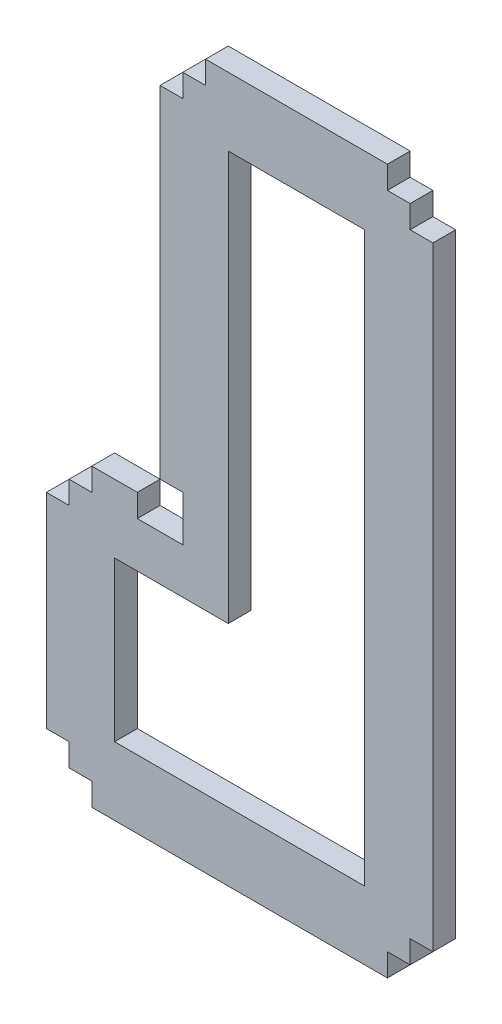
SolidWorks part; units mm, degrees
ref_plane "Front Plane" through (0, 0, 0) normal (0, 0, 1) x (1, 0, 0)
ref_plane "Top Plane" through (0, 0, 0) normal (0, 1, 0) x (1, 0, 0)
ref_plane "Right Plane" through (0, 0, 0) normal (1, 0, 0) x (0, 0, -1)
sketch "Sketch1" plane through (0, 0, 0) normal (0, 0, 1) x (1, 0, 0)
  line L0 (12.7, -69.85) -> (19.05, -69.85)
  line L1 (101.6, -69.85) -> (19.05, -69.85) construction
  line L2 (107.95, -76.2) -> (107.95, 120.65) construction
  line L3 (107.95, -69.85) -> (107.95, -63.5)
  line L4 (107.95, 114.3) -> (101.6, 114.3)
  line L5 (44.45, 114.3) -> (44.45, 107.95)
  line L6 (44.45, 0) -> (31.75, 0)
  line L7 (12.7, 0) -> (12.7, -6.35)
  line L8 (101.6, -76.2) -> (19.05, -76.2) construction
  line L9 (107.95, 107.95) -> (107.95, 114.3)
  line L10 (19.05, -69.85) -> (19.05, -76.2)
  line L11 (19.05, -76.2) -> (101.6, -76.2)
  line L12 (101.6, -69.85) -> (101.6, -76.2)
  line L13 (114.3, -69.85) -> (114.3, -76.2) construction
  line L14 (107.95, -63.5) -> (114.3, -63.5)
  line L15 (12.7, -63.5) -> (12.7, -69.85)
  line L16 (107.95, 107.95) -> (114.3, 107.95)
  line L17 (114.3, -63.5) -> (114.3, 107.95)
  line L18 (50.8, 120.65) -> (101.6, 120.65) construction
  line L20 (101.6, 114.3) -> (101.6, 120.65)
  line L21 (101.6, 120.65) -> (50.8, 120.65)
  line L22 (50.8, 114.3) -> (50.8, 120.65)
  line L23 (38.1, 114.3) -> (38.1, 31.75) construction
  line L24 (44.45, 107.95) -> (38.1, 107.95)
  line L25 (50.8, 114.3) -> (44.45, 114.3)
  line L26 (44.45, 12.7) -> (38.1, 12.7)
  line L27 (38.1, 107.95) -> (38.1, 12.7)
  line L28 (-38.1, 6.35) -> (6.35, 6.35) construction
  line L29 (12.7, -63.5) -> (6.35, -63.5)
  line L30 (19.05, 0) -> (12.7, 0)
  line L31 (12.7, -6.35) -> (6.35, -6.35)
  line L32 (6.35, -63.5) -> (6.35, -6.35)
  line L33 (44.45, 12.7) -> (44.45, 0)
  line L34 (19.05, 0) -> (19.05, 6.35)
  line L35 (19.05, 6.35) -> (31.75, 6.35)
  line L36 (31.75, 0) -> (31.75, 6.35)
  line L37 (101.6, -69.85) -> (107.95, -69.85)
  dimension "D1" = 6.35
  dimension "D2" = 6.35
  dimension "D3" = 6.35
  dimension "D4" = 6.35
  dimension "D5" = 6.35
  dimension "D6" = 6.35
  dimension "D7" = 6.35
  dimension "D8" = 6.35
  dimension "D9" = 6.35
  dimension "D10" = 6.35
extrude "Boss-Extrude1" add sketch "Sketch1" against normal blind 6.35 from offset 3.175 offset against normal yes
sketch "Sketch2" plane through (0, 0, -3.175) normal (0, 0, 1) x (1, 0, 0)
  line L0 (12.7, -69.85) -> (107.95, -69.85) construction
  line L1 (107.95, -69.85) -> (107.95, 114.3) construction
  line L2 (107.95, 114.3) -> (44.45, 114.3) construction
  line L3 (44.45, 114.3) -> (44.45, 0) construction
  line L4 (44.45, 0) -> (12.7, 0) construction
  line L5 (12.7, 0) -> (12.7, -69.85) construction
  line L6 (25.4, -57.15) -> (95.25, -57.15)
  line L7 (95.25, -57.15) -> (95.25, 101.6)
  line L8 (95.25, 101.6) -> (57.15, 101.6)
  line L9 (57.15, 101.6) -> (57.15, -12.7)
  line L10 (57.15, -12.7) -> (25.4, -12.7)
  line L11 (25.4, -12.7) -> (25.4, -57.15)
  dimension "D1" = 12.7
extrude "Cut-Extrude1" cut sketch "Sketch2" against normal through all
